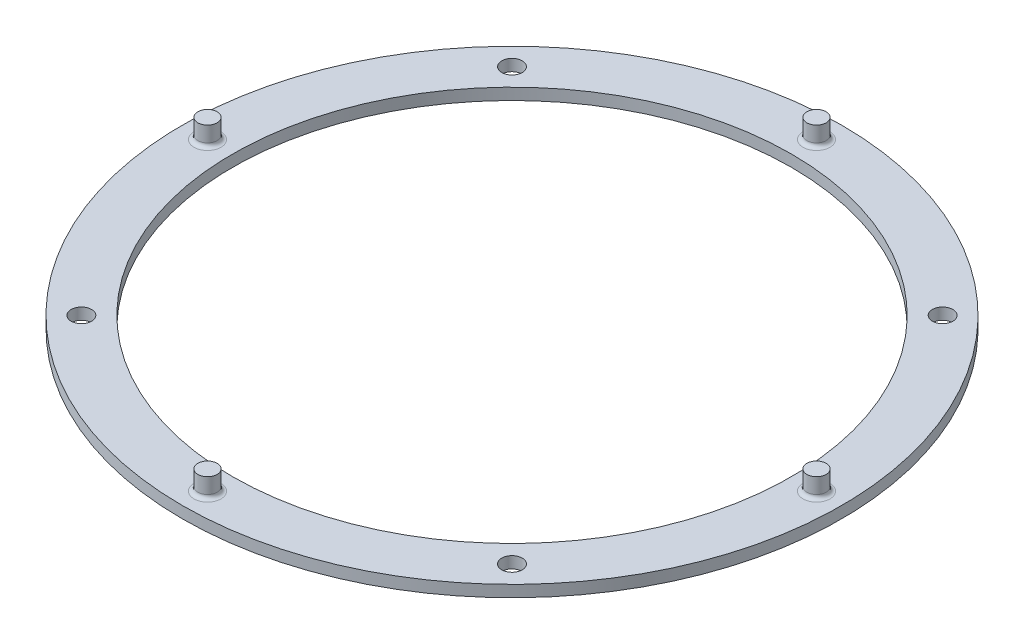
SolidWorks part; units mm, degrees
ref_plane "前视基准面" through (0, 0, 0) normal (0, 0, 1) x (1, 0, 0)
ref_plane "上视基准面" through (0, 0, 0) normal (0, 1, 0) x (1, 0, 0)
ref_plane "右视基准面" through (0, 0, 0) normal (1, 0, 0) x (0, 0, -1)
other "Configuration Table"
sketch "草图1" plane through (0, 0, 0) normal (0, 1, 0) x (1, 0, 0)
  circle A0 centre (0, 0) radius 72.5
  circle A1 centre (0, 0) radius 85.5
  dimension "D1" = 145
  dimension "D2" = 171
extrude "凸台-拉伸1" add sketch "草图1" along normal blind 3
sketch "草图2" plane through (0, 3, 0) normal (0, 1, 0) x (1, 0, 0)
  circle A0 centre (0, 0) radius 79
  circle A1 centre (0, 79) radius 2.5
  circle A2 centre (79, 0) radius 2.5
  circle A3 centre (0, -79) radius 2.5
  circle A4 centre (-79, 0) radius 2.5
  point P5 (0, 0)
  point P14 (0, 0)
  dimension "D1" = 158
  dimension "D2" = 5
  dimension "D3" = 4
extrude "凸台-拉伸4" add sketch "草图2" along normal blind 5 contours A1 | A4 | A2 | A3
fillet "圆角1" radius 1 4 edges at (79, 3, 2.5) (0, 3, -76.5) (-79, 3, 2.5) (0, 3, 81.5)
sketch "草图3" plane through (0, 3, 0) normal (0, 1, 0) x (1, 0, 0)
  circle A0 centre (0, 0) radius 79
  circle A1 centre (0, 79) radius 2.65
  circle A2 centre (55.8614, 55.8614) radius 2.65
  circle A3 centre (79, 0) radius 2.65
  circle A4 centre (55.8614, -55.8614) radius 2.65
  circle A5 centre (0, -79) radius 2.65
  circle A6 centre (-55.8614, -55.8614) radius 2.65
  circle A7 centre (-79, 0) radius 2.65
  circle A8 centre (-55.8614, 55.8614) radius 2.65
  point P22 (0, 0)
  dimension "D1" = 5.3
  dimension "D2" = 8
extrude "切除-拉伸1" cut sketch "草图3" against normal blind 5 contours A8 | A6 | A4 | A2
